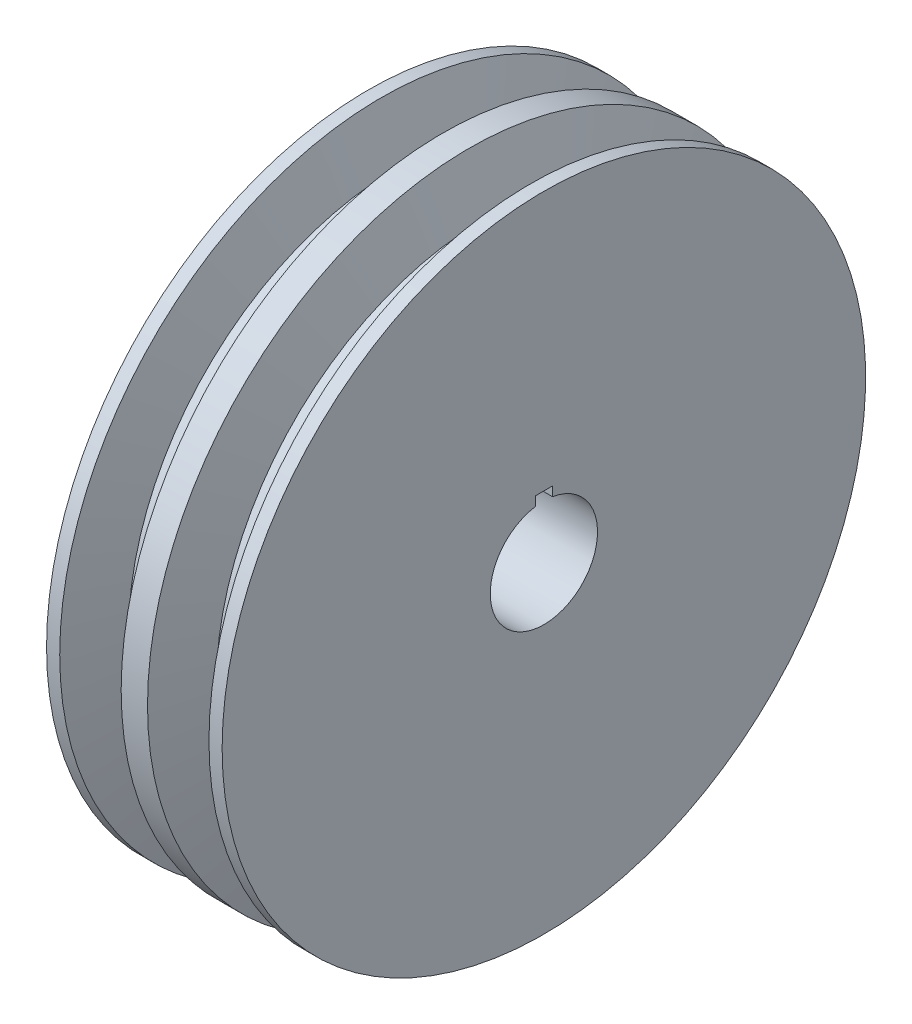
SolidWorks part; units mm, degrees
ref_plane "Ön Düzlem" through (0, 0, 0) normal (0, 0, 1) x (1, 0, 0)
ref_plane "Üst Düzlem" through (0, 0, 0) normal (0, 1, 0) x (1, 0, 0)
ref_plane "Sağ Düzlem" through (0, 0, 0) normal (1, 0, 0) x (0, 0, -1)
ref_plane "Düzlem1" through (0, 0, 379.673) normal (0, 0, -1) x (-1, 0, 0)
sketch "Çizim1" plane through (0, 0, 379.673) normal (0, 0, -1) x (-1, 0, 0)
  line L0 (-2016.209, 150) -> (-2016.209, 0)
  line L1 (-2016.209, 0) -> (-1934.3536, 0)
  line L2 (-1934.3536, 0) -> (-1934.3536, 150)
  line L3 (-1934.3536, 150) -> (-1940.4928, 150)
  line L4 (-1940.4928, 150) -> (-1948.0005, 125.4434)
  line L5 (-1948.0005, 125.4434) -> (-1961.6344, 125.4434)
  line L6 (-1961.6344, 125.4434) -> (-1969.1421, 150)
  line L7 (-1969.1421, 150) -> (-1981.4205, 150)
  line L8 (-1981.4205, 150) -> (-1988.9282, 125.4434)
  line L9 (-1988.9282, 125.4434) -> (-2002.5621, 125.4434)
  line L10 (-2002.5621, 125.4434) -> (-2010.0698, 150)
  line L11 (-2010.0698, 150) -> (-2016.209, 150)
  line L12 (-2016.209, 0) -> (-1934.3536, 0) construction
  dimension "D1" = 150
revolve "Döndür1" add sketch "Çizim1" angle 360 about L12
sketch "Çizim2" plane through (1934.3536, 0, 0) normal (-1, 0, 0) x (0, 0, 1)
  circle A0 centre (379.673, 0) radius 20
extrude "Kes-Ekstrüzyon1" cut sketch "Çizim2" against normal blind 160
sketch "Çizim3" plane through (2016.209, 0, 0) normal (1, 0, 0) x (0, 0, -1)
  circle A0 centre (-379.673, 0) radius 25
extrude "Kes-Ekstrüzyon2" cut sketch "Çizim3" against normal blind 120
sketch "Çizim4" plane through (2016.209, 0, 0) normal (1, 0, 0) x (0, 0, -1)
  line L0 (-379.673, 0) -> (-379.673, 25)
  line L1 (-379.673, 25) -> (-379.673, 29)
  line L2 (-379.673, 29) -> (-375.673, 29)
  line L3 (-379.673, 29) -> (-383.673, 29)
  line L4 (-383.673, 29) -> (-383.673, 24.6779)
  line L5 (-375.673, 29) -> (-375.673, 24.6779)
  circle A0 centre (-379.673, 0) radius 25 construction
  circle M4 centre (-379.673, 0) radius 25
extrude "Kes-Ekstrüzyon3" cut sketch "Çizim4" against normal blind 120 contours L5 L2 L1 M4 | L3 L4 L1 M4
